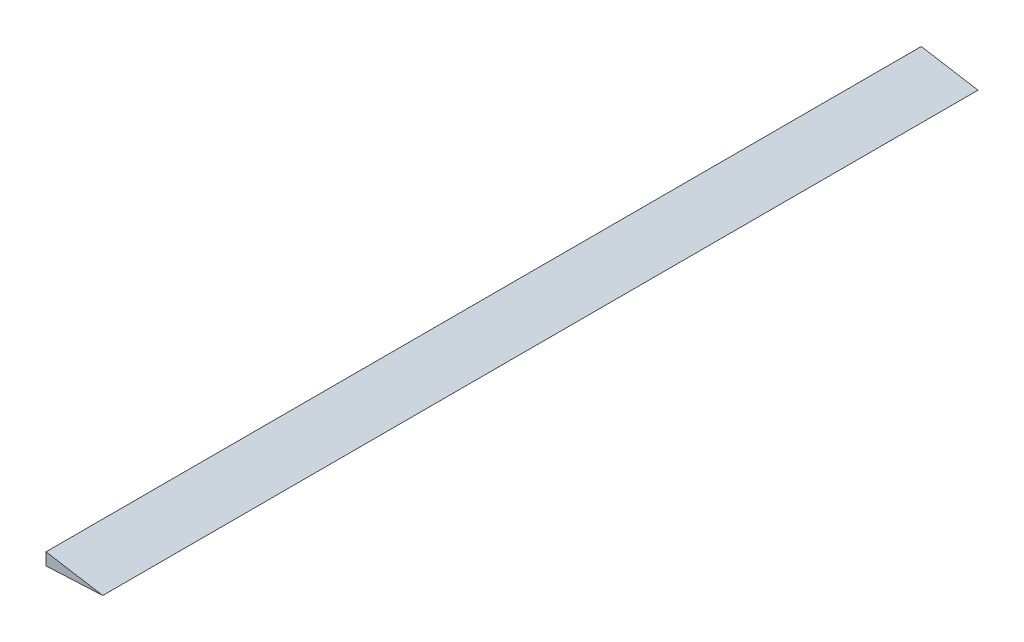
SolidWorks part; units mm, degrees
material "Balsa"
ref_plane "Front Plane" through (0, 0, 0) normal (0, 0, 1) x (1, 0, 0)
ref_plane "Top Plane" through (0, 0, 0) normal (0, 1, 0) x (1, 0, 0)
ref_plane "Right Plane" through (0, 0, 0) normal (1, 0, 0) x (0, 0, -1)
sketch "Sketch1" plane through (0, 0, 0) normal (0, 0, 1) x (1, 0, 0)
  line L0 (306.8496, -2.5161) -> (306.8496, 8.4499) construction
  line L1 (306.8496, -2.5161) -> (306.8496, 8.4499)
  line L2 (306.8496, 8.4499) -> (357.6496, 0)
  line L3 (306.8496, -2.5161) -> (357.6496, 0)
  spline S0 degree 3 poles (354.9573, 0.0431) (358.3317, -0.0432) (354.9981, 0.2938) (352.3707, 0.8024) (346.1763, 1.8676) (338.7813, 3.2655) (329.3081, 4.8919) (318.2482, 6.6648) (305.5952, 8.6507) (291.564, 10.8193) (276.34, 13.1505) (260.1392, 15.5903) (243.1815, 18.0913) (225.699, 20.6027) (207.9209, 23.0318) (190.087, 25.3152) (172.4086, 27.3328) (155.0467, 28.9096) (138.1258, 29.947) (121.7437, 30.3922) (105.9899, 30.2108) (90.9433, 29.4155) (76.6903, 28.0308) (63.3272, 26.1868) (50.9728, 23.9485) (39.7523, 21.3791) (29.7714, 18.545) (21.1318, 15.5018) (13.8914, 12.3237) (8.1391, 9.1075) (3.8158, 5.9031) (1.1802, 2.9693) (-0.4877, -0.018) (1.2572, -2.9285) (4.805, -4.6528) (9.8754, -6.6365) (16.78, -8.2511) (25.3535, -9.7017) (35.5828, -10.8813) (47.3622, -11.8027) (60.5842, -12.4624) (75.1117, -12.8607) (90.7897, -13.0132) (107.4435, -12.9137) (124.9052, -12.5651) (143.0256, -11.8868) (161.6617, -10.9405) (180.6424, -9.8572) (199.7442, -8.7119) (218.721, -7.5525) (237.3263, -6.4253) (255.3201, -5.3536) (272.4652, -4.367) (288.5372, -3.4753) (303.3148, -2.6922) (316.6121, -2.0207) (328.2104, -1.4385) (338.1246, -0.9102) (345.8395, -0.4061) (352.2525, -0.129) (354.9573, 0.0431) (358.3317, -0.0432) (354.9981, 0.2938) knots -0.015092 -0.006889 -0.001754 0 0.001748 0.006827 0.01488 0.025572 0.038694 0.054171 0.071834 0.091435 0.112685 0.135293 0.158944 0.183315 0.20807 0.232879 0.257399 0.281384 0.304706 0.327241 0.348897 0.369607 0.389308 0.407886 0.425177 0.441027 0.4553 0.467904 0.478752 0.487814 0.49509 0.500617 0.504451 0.507804 0.513091 0.520546 0.530249 0.542214 0.556382 0.572656 0.590895 0.610925 0.632536 0.655496 0.679547 0.704499 0.730211 0.756436 0.782837 0.809062 0.834776 0.859641 0.883338 0.905541 0.925965 0.944326 0.960366 0.973929 0.984908 0.993111 0.998246 1 1.001748 1.006827 1.01488 only from (357.6496, 0) to (357.6496, 0) construction
  spline S1 degree 3 poles (354.9573, 0.0431) (358.3317, -0.0432) (354.9981, 0.2938) (352.3707, 0.8024) (346.1763, 1.8676) (338.7813, 3.2655) (329.3081, 4.8919) (318.2482, 6.6648) (305.5952, 8.6507) (291.564, 10.8193) (276.34, 13.1505) (260.1392, 15.5903) (243.1815, 18.0913) (225.699, 20.6027) (207.9209, 23.0318) (190.087, 25.3152) (172.4086, 27.3328) (155.0467, 28.9096) (138.1258, 29.947) (121.7437, 30.3922) (105.9899, 30.2108) (90.9433, 29.4155) (76.6903, 28.0308) (63.3272, 26.1868) (50.9728, 23.9485) (39.7523, 21.3791) (29.7714, 18.545) (21.1318, 15.5018) (13.8914, 12.3237) (8.1391, 9.1075) (3.8158, 5.9031) (1.1802, 2.9693) (-0.4877, -0.018) (1.2572, -2.9285) (4.805, -4.6528) (9.8754, -6.6365) (16.78, -8.2511) (25.3535, -9.7017) (35.5828, -10.8813) (47.3622, -11.8027) (60.5842, -12.4624) (75.1117, -12.8607) (90.7897, -13.0132) (107.4435, -12.9137) (124.9052, -12.5651) (143.0256, -11.8868) (161.6617, -10.9405) (180.6424, -9.8572) (199.7442, -8.7119) (218.721, -7.5525) (237.3263, -6.4253) (255.3201, -5.3536) (272.4652, -4.367) (288.5372, -3.4753) (303.3148, -2.6922) (316.6121, -2.0207) (328.2104, -1.4385) (338.1246, -0.9102) (345.8395, -0.4061) (352.2525, -0.129) (354.9573, 0.0431) (358.3317, -0.0432) (354.9981, 0.2938) knots -0.015092 -0.006889 -0.001754 0 0.001748 0.006827 0.01488 0.025572 0.038694 0.054171 0.071834 0.091435 0.112685 0.135293 0.158944 0.183315 0.20807 0.232879 0.257399 0.281384 0.304706 0.327241 0.348897 0.369607 0.389308 0.407886 0.425177 0.441027 0.4553 0.467904 0.478752 0.487814 0.49509 0.500617 0.504451 0.507804 0.513091 0.520546 0.530249 0.542214 0.556382 0.572656 0.590895 0.610925 0.632536 0.655496 0.679547 0.704499 0.730211 0.756436 0.782837 0.809062 0.834776 0.859641 0.883338 0.905541 0.925965 0.944326 0.960366 0.973929 0.984908 0.993111 0.998246 1 1.001748 1.006827 1.01488 only from (357.6496, 0) to (357.6496, 0)
sketch "Sketch2" plane through (0, 0, -761.9997) normal (0, 0, -1) x (-1, 0, 0)
  line L0 (-306.8496, -2.5161) -> (-306.8496, 8.4499) construction
  line L1 (-306.8496, -2.5161) -> (-357.6496, 0) construction
  line L2 (-306.8496, 8.4499) -> (-357.6496, 0) construction
  line L3 (-306.8496, -2.5161) -> (-306.8496, 8.4499)
  line L4 (-306.8496, -2.5161) -> (-357.6496, 0)
  line L5 (-306.8496, 8.4499) -> (-357.6496, 0)
extrude "Boss-Extrude2" add sketch "Sketch2" against normal blind 783.336
